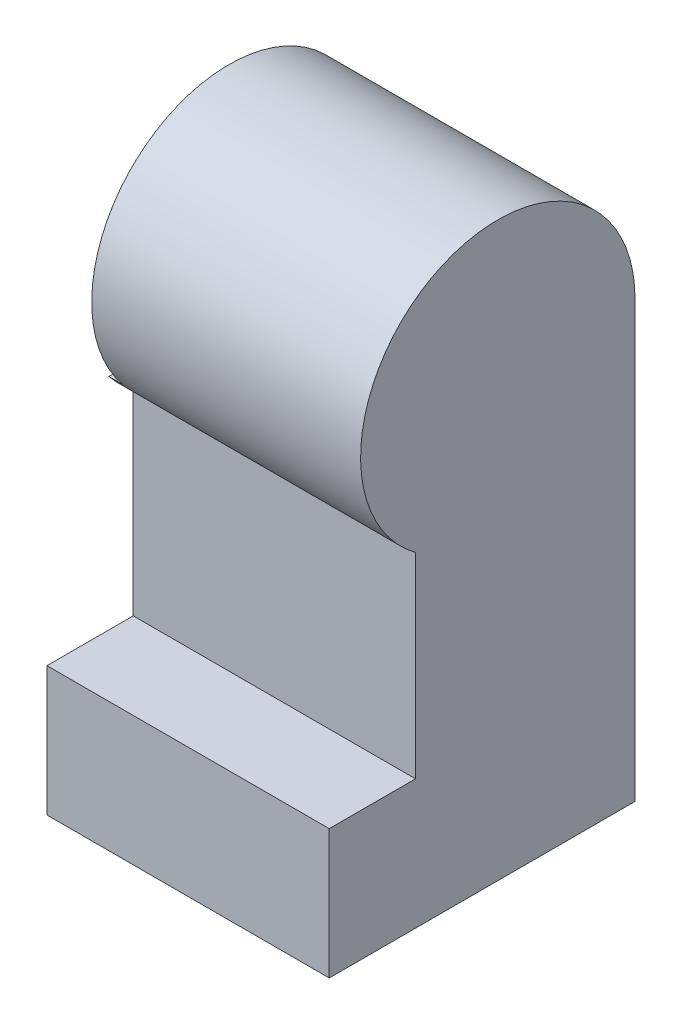
SolidWorks part; units mm, degrees
ref_plane "Alzado" through (0, 0, 0) normal (0, 0, 1) x (1, 0, 0)
ref_plane "Planta" through (0, 0, 0) normal (0, 1, 0) x (1, 0, 0)
ref_plane "Vista lateral" through (0, 0, 0) normal (1, 0, 0) x (0, 0, -1)
sketch "Croquis2" plane through (0, 0, 0) normal (1, 0, 0) x (0, 0, -1)
  line L0 (11.7, 11.4) -> (11.7, -21.9)
  line L1 (11.7, -21.9) -> (-11.7, -21.9)
  line L2 (-11.7, -21.9) -> (-11.7, -12)
  line L3 (-11.7, -12) -> (-5.1, -12)
  line L4 (-5.1, -12) -> (-5.1, 3)
  arc A0 (11.7, 11.4) -> (-5.1, 3) centre (1.2, 11.4) ccw
  dimension "D1" = 21
  dimension "D2" = 33.3
  dimension "D3" = 15
  dimension "D4" = 23.4
  dimension "D5" = 16.8
  dimension "D6" = 21.9
  dimension "D7" = 11.7
extrude "Saliente-Extruir1" add sketch "Croquis2" along normal mid plane 21.6
sketch "Croquis4" plane through (0, 0, 0) normal (0, 0, 1) x (1, 0, 0)
  line L1 (-10.8, 21.9) -> (-9.775, 21.9)
  line L2 (-10.8, 21.9) -> (-10.8, 4.8)
  line L3 (-10.8, 4.8) -> (-9.775, 4.8)
  line L4 (-9.775, 21.9) -> (-9.775, 4.8)
  dimension "D1" = 17.1
  dimension "D2" = 1.025
extrude "Cortar-Extruir1" cut sketch "Croquis4" against normal through all both and the other way through all
sketch "Croquis5" plane through (-9.775, 0, 0) normal (-1, 0, 0) x (0, 0, 1)
  line L0 (-11.7, 4.8) -> (6.9664, 4.8) construction
  line L1 (-11.7, -21.9) -> (-11.7, 4.8) construction
  circle A0 centre (0, 13.35) radius 3
  dimension "D1" = 6
  dimension "D3" = 11.7
  dimension "D2" = 8.55
extrude "Cortar-Extruir2" cut sketch "Croquis5" against normal blind 5.4 and the other way through all
